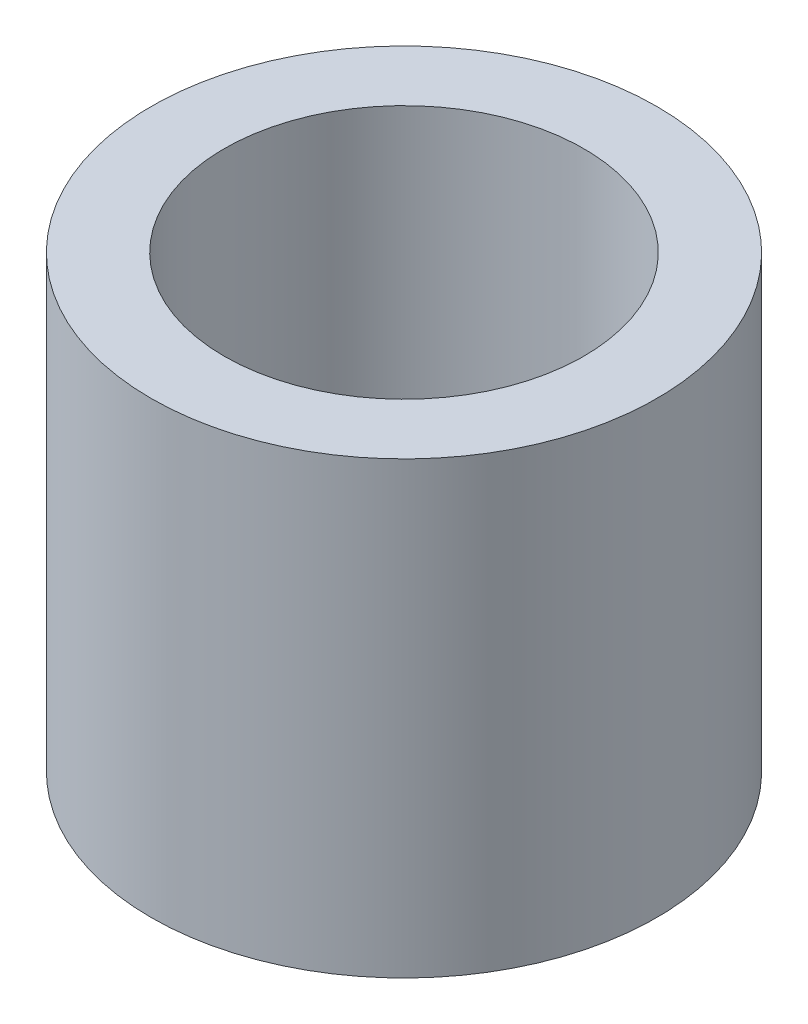
SolidWorks part; units mm, degrees
ref_plane "Front Plane" through (0, 0, 0) normal (0, 0, 1) x (1, 0, 0)
ref_plane "Top Plane" through (0, 0, 0) normal (0, 1, 0) x (1, 0, 0)
ref_plane "Right Plane" through (0, 0, 0) normal (1, 0, 0) x (0, 0, -1)
sketch "Sketch1" plane through (0, 0, 0) normal (0, 1, 0) x (1, 0, 0)
  circle A0 centre (0, 0) radius 1.6
  circle A1 centre (0, 0) radius 2.25
  dimension "D1" = 4.5
  dimension "D2" = 3.2
extrude "Boss-Extrude1" add sketch "Sketch1" along normal blind 4
